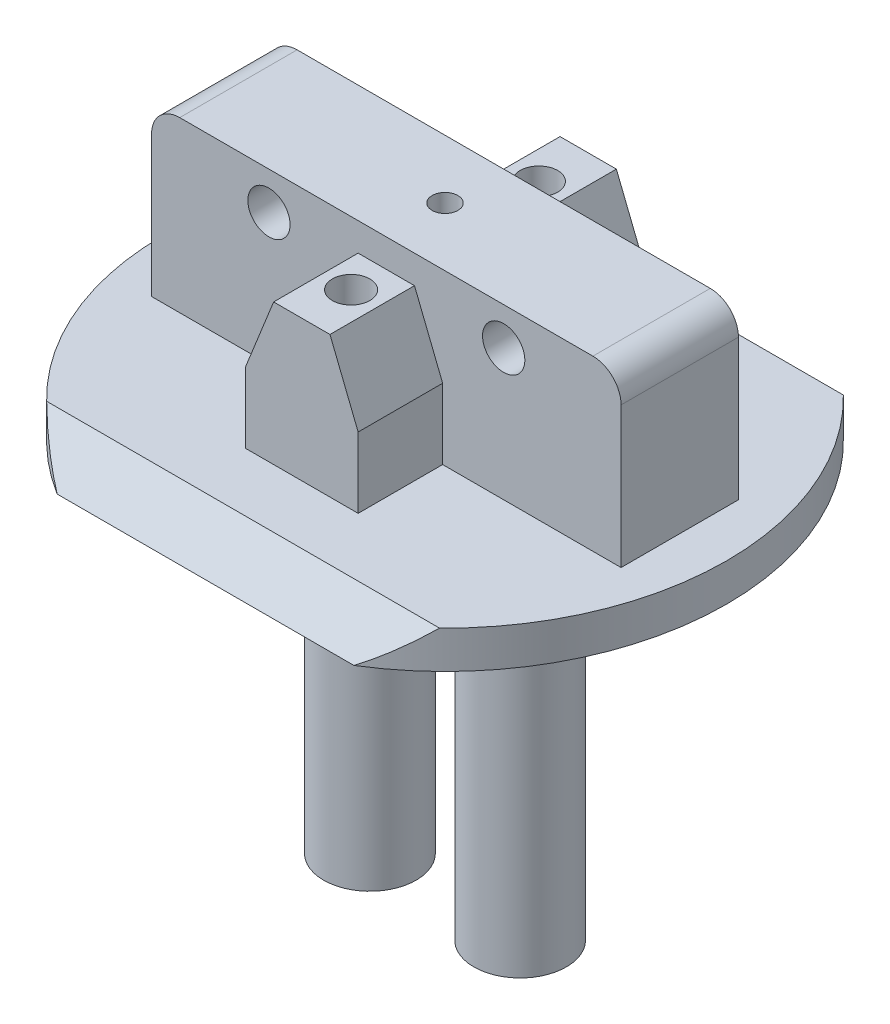
SolidWorks part; units mm, degrees
ref_plane "Front Plane" through (0, 0, 0) normal (0, 0, 1) x (1, 0, 0)
ref_plane "Top Plane" through (0, 0, 0) normal (0, 1, 0) x (1, 0, 0)
ref_plane "Right Plane" through (0, 0, 0) normal (1, 0, 0) x (0, 0, -1)
sketch "Sketch1" plane through (0, 0, 0) normal (0, 1, 0) x (1, 0, 0)
  circle A0 centre (0, 0) radius 30
extrude "Boss-Extrude1" add sketch "Sketch1" along normal blind 4
sketch "Sketch2" plane through (0, 0, 0) normal (1, 0, 0) x (0, 0, -1)
  line L0 (0, 4) -> (21.5, 4)
  line L1 (30, 4) -> (-30, 4) construction
  line L3 (0, 4) -> (-21.5, 4)
  line L5 (0, 4) -> (0, 19.5) construction
  line L6 (-9, 16.5) -> (-21.5, 4)
  line L7 (-9, 16.5) -> (9, 16.5)
  line L9 (9, 16.5) -> (21.5, 4)
  dimension "D1" = 12.5
  dimension "D2" = 45
  dimension "D3" = 21.5
  dimension "D4" = 21.5
  dimension "D5" = 45
sketch "Sketch3" plane through (0, 4, 0) normal (0, 1, 0) x (1, 0, 0)
  circle A0 centre (0, 0) radius 21.5
  dimension "D1" = 43
extrude "Boss-Extrude2" add sketch "Sketch2" along normal up to surface and the other way up to surface up to face at (0, 4, 30) other way up to face at (0, 4, 30)
ref_plane "Plane1" through (0, 12.75, -12.75) normal (0, 0.7071, -0.7071) x (1, 0, 0)
other "SurfaceCut1"
ref_plane "Plane2" through (0, 12.75, 12.75) normal (0, 0.7071, 0.7071) x (1, 0, 0)
other "SurfaceCut2"
extrude "Cut-Extrude2" cut sketch "Sketch3" against normal up to surface (12.5 mm away) flip side to cut contours A0
sketch "Sketch5" plane through (0, 0, 0) normal (0, -1, 0) x (-1, 0, 0)
  line L0 (0, 0) -> (0, -6)
  line L1 (0, -6) -> (-17.5, -6)
  line L2 (-17.5, -6) -> (-17.5, 6)
  line L3 (-17.5, 6) -> (17.5, 6)
  line L4 (17.5, 6) -> (17.5, -6)
  line L5 (17.5, -6) -> (0, -6)
  circle A0 centre (0, 0) radius 6
  circle A1 centre (0, 0) radius 3.5
  dimension "D1" = 12
  dimension "D2" = 7
  dimension "D3" = 12
  dimension "D4" = 6
  dimension "D5" = 35
  dimension "D6" = 17.5
extrude "Boss-Extrude3" add sketch "Sketch5" along normal blind 18 contours L1 L2 L3 L4 L5
sketch "Sketch6" plane through (0, 0, 0) normal (0, -1, 0) x (1, 0, 0)
  line L0 (0, 6) -> (0, 15) construction
  line L1 (-17.5, 6) -> (17.5, 6) construction
  line L2 (0, 15) -> (7, 15)
  line L3 (7, 15) -> (7, 6)
  line L4 (-17.5, 6) -> (17.5, 6) construction
  line L5 (7, 6) -> (-7, 6)
  line L6 (-7, 6) -> (-7, 15)
  line L7 (-7, 15) -> (0, 15)
  dimension "D1" = 14
  dimension "D2" = 9
extrude "Boss-Extrude4" add sketch "Sketch6" along normal blind 15 contours L7 L2 L3 L5 L6
sketch "Sketch7" plane through (0, 0, 0) normal (0, -1, 0) x (1, 0, 0)
  line L0 (0, -6) -> (0, -15) construction
  line L1 (17.5, -6) -> (-17.5, -6) construction
  line L2 (0, -15) -> (7, -15)
  line L3 (7, -15) -> (7, -6)
  line L4 (7, -6) -> (-7, -6)
  line L7 (-7, -6) -> (-7, -15)
  line L8 (-7, -15) -> (0, -15)
  dimension "D1" = 9
  dimension "D2" = 14
extrude "Boss-Extrude5" add sketch "Sketch7" along normal blind 15
sketch "Sketch8" plane through (0, 0, 0) normal (0, 0, 1) x (1, 0, 0)
  line L0 (0, 0) -> (12.5, 0) construction
  line L1 (12.5, 0) -> (12.5, -12.5) construction
  line L2 (12.5, -12.5) -> (-12.5, -12.5) construction
  line L3 (-12.5, -12.5) -> (-12.5, 0) construction
  line L4 (-12.5, 0) -> (0, 0) construction
  circle A0 centre (-12.5, -12.5) radius 2
  circle A1 centre (12.5, -12.5) radius 2
  dimension "D4" = 4
  dimension "D5" = 4
  dimension "D1" = 12.5
  dimension "D2" = 25
  dimension "D3" = 12.5
extrude "Cut-Extrude3" cut sketch "Sketch8" against normal through all both and the other way through all contours A0 | A1
ref_plane "Plane3" through (0, -18, 0) normal (0, -1, 0) x (-1, 0, 0)
ref_plane "Plane4" through (10.366, -9.6749, -8.0624) normal (0.6355, -0.5931, -0.4943) x (-0.3613, 0.3373, -0.8693)
ref_plane "Plane5" through (-10.366, -9.6749, -8.0624) normal (0.6355, 0.5931, 0.4943) x (0.3613, 0.3373, -0.8693)
ref_plane "Plane6" through (10.366, -9.6749, 8.0624) normal (-0.6355, 0.5931, -0.4943) x (-0.3613, 0.3373, 0.8693)
ref_plane "Plane7" through (-10.366, -9.6749, 8.0624) normal (0.6355, 0.5931, -0.4943) x (-0.3613, -0.3373, -0.8693)
ref_plane "Plane9" through (0, 0, 6) normal (0, 0, 1) x (1, 0, 0)
sketch "Sketch16" plane through (0, 0, 6) normal (0, 0, 1) x (1, 0, 0)
  line L0 (17.5, -18) -> (17.5, -14.5)
  line L1 (-6.6, -18) -> (6.6, -18) construction
  line L2 (17.5, -18) -> (17.5, 0) construction
  line L3 (17.5, -18) -> (14, -18)
  line L4 (17.5, -14.5) -> (14, -18)
  line L5 (-17.5, -18) -> (-14, -18)
  line L6 (-17.5, -18) -> (-17.5, 0) construction
  line L7 (-14, -18) -> (-17.5, -14.5)
  line L8 (-17.5, -14.5) -> (-17.5, -18)
  dimension "D2" = 3.5
extrude "Cut-Extrude8" cut sketch "Sketch16" against normal through all both and the other way through all
sketch "Sketch17" plane through (10.366, -9.6749, -8.0624) normal (0.6355, -0.5931, -0.4943) x (-0.3613, 0.3373, -0.8693)
  line L0 (-2.3725, -6.1896) -> (7.9806, -0.7067)
  line L1 (5.4512, -6.1896) -> (10.5101, 4.7762) construction
  line L2 (7.9806, -0.7067) -> (7.9806, -10.9658)
  line L3 (10.5101, -15.7421) -> (5.4512, -6.1896) construction
  line L4 (7.9806, -10.9658) -> (-2.3725, -6.1896)
extrude "Cut-Extrude9" cut sketch "Sketch17" along normal through all
sketch "Sketch19" plane through (-10.366, -9.6749, -8.0624) normal (0.6355, 0.5931, 0.4943) x (0.3613, 0.3373, -0.8693)
  line L0 (-2.3725, -6.1896) -> (7.9806, -10.9658)
  line L1 (7.9806, -10.9658) -> (7.9806, -0.7067)
  line L2 (5.4512, -6.1896) -> (10.5101, 4.7762) construction
  line L3 (7.9806, -0.7067) -> (-2.3725, -6.1896)
extrude "Cut-Extrude11" cut sketch "Sketch19" against normal blind 20 contours L3 L0 L1
sketch "Sketch20" plane through (-10.366, -9.6749, 8.0624) normal (0.6355, 0.5931, -0.4943) x (-0.3613, -0.3373, -0.8693)
  line L0 (2.3725, -6.1896) -> (-7.9806, -0.7067)
  line L1 (-5.4512, -6.1896) -> (-10.5101, 4.7762) construction
  line L2 (-7.9806, -0.7067) -> (-7.9806, -10.9658)
  line L3 (-5.4512, -6.1896) -> (-10.5101, -15.7421) construction
  line L4 (-7.9806, -10.9658) -> (2.3725, -6.1896)
extrude "Cut-Extrude12" cut sketch "Sketch20" against normal blind 20
sketch "Sketch21" plane through (10.366, -9.6749, 8.0624) normal (-0.6355, 0.5931, -0.4943) x (-0.3613, 0.3373, 0.8693)
  line L0 (-2.3725, -6.1896) -> (7.9806, -0.7067)
  line L1 (5.4512, -6.1896) -> (10.5101, 4.7762) construction
  line L2 (7.9806, -0.7067) -> (7.9806, -10.9658)
  line L3 (7.9806, -10.9658) -> (-2.3725, -6.1896)
extrude "Cut-Extrude13" cut sketch "Sketch21" against normal blind 20 contours L0 L2 L3
ref_plane "Plane10" through (0, 16.5, 0) normal (0, 1, 0) x (1, 0, 0)
sketch "Sketch25" plane through (0, 0, 0) normal (0, 0, 1) x (1, 0, 0)
  line L1 (-33.0377, 0) -> (33.0377, 0)
  line L2 (-33.0377, 0) -> (-33.0377, -20.1422)
  line L3 (-33.0377, -20.1422) -> (33.0377, -20.1422)
  line L4 (33.0377, 0) -> (33.0377, -20.1422)
  dimension "D1" = 20.1422
  dimension "D2" = 66.0754
extrude "Cut-Extrude14" cut sketch "Sketch25" along normal through all both and the other way through all
sketch "Sketch26" plane through (0, 16.5, 0) normal (0, 1, 0) x (1, 0, 0)
  line L0 (-12.1, 0) -> (12.1, 0) construction
  circle A0 centre (-8, 0) radius 5
  circle A2 centre (8, 0) radius 5
  dimension "D1" = 10
  dimension "D2" = 10
  dimension "D3" = 8
  dimension "D4" = 8
sketch "Sketch27" plane through (0, 16.5, 0) normal (0, 1, 0) x (1, 0, 0)
  line L0 (0, -9.075) -> (0, 9.075) construction
  circle A0 centre (0, 0) radius 1.375
  dimension "D1" = 2.75
  dimension "D2" = 0
extrude "Cut-Extrude16" cut sketch "Sketch27" against normal blind 30
sketch "Sketch28" plane through (0, 0, 0) normal (0, -1, 0) x (1, 0, 0)
  line L0 (0, -9.075) -> (0, 9.075) construction
  line L1 (9.075, 0) -> (-9.075, 0) construction
  circle A0 centre (0, -15) radius 5
  circle A1 centre (22, 0) radius 5
  circle A2 centre (0, 15) radius 5
  circle A3 centre (-22, 0) radius 5
  circle A4 centre (-14, 12) radius 5
  circle A5 centre (14, 12) radius 5
  circle A6 centre (14, -12) radius 5
  circle A7 centre (-14, -12) radius 5
  dimension "D1" = 10
  dimension "D2" = 10
  dimension "D3" = 10
  dimension "D4" = 10
  dimension "D5" = 10
  dimension "D6" = 10
  dimension "D7" = 10
  dimension "D10" = 10
  dimension "D11" = 15
  dimension "D8" = 22
  dimension "D9" = 22
  dimension "D12" = 15
  dimension "D13" = 14
  dimension "D14" = 14
  dimension "D15" = 14
  dimension "D16" = 14
  dimension "D17" = 12
  dimension "D18" = 12
  dimension "D19" = 12
  dimension "D20" = 12
extrude "Cut-Extrude17" cut sketch "Sketch28" against normal blind 3
sketch "Sketch29" plane through (0, 0, 0) normal (1, 0, 0) x (0, 0, -1)
  line L0 (-10.55, 14.95) -> (-14.95, 10.55) construction
  line L1 (-21.5, 4) -> (21.9126, 4)
  line L2 (-21.5, 4) -> (-21.5, 17.3262)
  line L3 (-21.5, 17.3262) -> (21.9126, 17.3262)
  line L4 (21.9126, 4) -> (21.9126, 17.3262)
  line L5 (21.5, 4) -> (-21.5, 4) construction
extrude "Cut-Extrude18" cut sketch "Sketch29" against normal through all both and the other way through all
sketch "Sketch32" plane through (0, 4, 0) normal (0, 1, 0) x (1, 0, 0)
  line L1 (-25, 6.25) -> (25, 6.25)
  line L2 (-25, 6.25) -> (-25, -6.25)
  line L3 (-25, -6.25) -> (25, -6.25)
  line L4 (25, 6.25) -> (25, -6.25)
  line L5 (-25, 6.25) -> (25, -6.25) construction
  line L6 (-25, -6.25) -> (25, 6.25) construction
  point P0 (0, 0)
  dimension "D1" = 12.5
  dimension "D2" = 50
extrude "Boss-Extrude6" add sketch "Sketch32" along normal blind 18
sketch "Sketch35" plane through (0, 0, -6.25) normal (0, 0, -1) x (-1, 0, 0)
  line L0 (-20.9225, 4) -> (20.9225, 4) construction
  line L1 (-6, 4) -> (6, 4)
  line L2 (-6, 4) -> (-6, 19)
  line L3 (-6, 19) -> (6, 19)
  line L4 (6, 4) -> (6, 19)
  line L5 (0, 9.075) -> (0, -9.075) construction
  dimension "D1" = 12
  dimension "D2" = 15
  dimension "D3" = 6
extrude "Boss-Extrude7" add sketch "Sketch35" along normal blind 9
sketch "Sketch36" plane through (0, 19, 0) normal (0, 1, 0) x (1, 0, 0)
  line L0 (0, -9.075) -> (0, 9.075) construction
  circle A0 centre (0, 10) radius 2
  dimension "D1" = 4
  dimension "D2" = 10
sketch "Sketch37" plane through (0, 0, -6.25) normal (0, 0, -1) x (-1, 0, 0)
  line L0 (0, 12.1) -> (0, -12.1) construction
  line L3 (-20.9225, 4) -> (20.9225, 4) construction
  line L4 (-6, 4) -> (6, 4) construction
  circle A0 centre (-12.5, 18) radius 2.25
  circle A1 centre (12.5, 18) radius 2.25
  dimension "D5" = 4.5
  dimension "D6" = 4.5
  dimension "D1" = 12.5
  dimension "D2" = 12.5
  dimension "D3" = 14
  dimension "D4" = 14
extrude "Cut-Extrude19" cut sketch "Sketch37" against normal through all both and the other way through all
extrude "Cut-Extrude20" cut sketch "Sketch36" against normal blind 15
sketch "Sketch39" plane through (0, 0, 6.25) normal (0, 0, 1) x (1, 0, 0)
  line L0 (-25, 4) -> (25, 4) construction
  line L1 (-6, 4) -> (6, 4)
  line L2 (-6, 4) -> (-6, 19)
  line L3 (-6, 19) -> (6, 19)
  line L4 (6, 4) -> (6, 19)
  line L5 (0, -12.1) -> (0, 12.1) construction
  dimension "D1" = 12
  dimension "D2" = 6
  dimension "D3" = 15
extrude "Boss-Extrude8" add sketch "Sketch39" along normal blind 9
sketch "Sketch40" plane through (0, 19, 0) normal (0, 1, 0) x (1, 0, 0)
  line L0 (0, -12.1) -> (0, 12.1) construction
  circle A0 centre (0, -10) radius 2
  dimension "D1" = 4
  dimension "D2" = 10
extrude "Cut-Extrude21" cut sketch "Sketch40" against normal blind 15
fillet "Fillet1" radius 3 1 edges at (25, 22, 0)
fillet "Fillet2" radius 3 1 edges at (-25, 22, 0)
sketch "Sketch44" plane through (0, 4, 0) normal (0, -1, 0) x (1, 0, 0)
  circle A0 centre (0, 0) radius 1.375
  dimension "D1" = 2.75
extrude "Cut-Extrude24" cut sketch "Sketch44" against normal blind 20
sketch "Sketch45" plane through (0, 0, 0) normal (0, -1, 0) x (1, 0, 0)
  circle A0 centre (-8, 0) radius 4.925
  circle A1 centre (8, 0) radius 4.925
  dimension "D1" = 9.85
  dimension "D2" = 9.85
extrude "Boss-Extrude9" add sketch "Sketch45" along normal blind 42
sketch "Sketch46" plane through (0, -42, 0) normal (0, -1, 0) x (1, 0, 0)
  circle A0 centre (-8, 0) radius 1.8923
  dimension "D1" = 3.7846
extrude "Cut-Extrude25" cut sketch "Sketch46" against normal blind 29.972
sketch "Sketch47" plane through (0, -42, 0) normal (0, -1, 0) x (1, 0, 0)
  circle A0 centre (8, 0) radius 1.8923
  dimension "D1" = 3.7846
extrude "Cut-Extrude26" cut sketch "Sketch47" against normal blind 29.972
sketch "Sketch58" plane through (0, 0, -15.25) normal (0, 0, -1) x (-1, 0, 0)
  line L0 (6, 19) -> (6, 11.5)
  line L1 (6, 4) -> (6, 19) construction
  line L2 (6, 11.5) -> (3, 19)
  line L3 (6, 19) -> (-6, 19) construction
  line L4 (3, 19) -> (6, 19)
  dimension "D1" = 3
extrude "Cut-Extrude32" cut sketch "Sketch58" against normal up to surface (9 mm away) up to face at (14.75, 18, -6.25)
sketch "Sketch59" plane through (0, 0, -15.25) normal (0, 0, -1) x (-1, 0, 0)
  line L0 (-6, 19) -> (-6, 11.5)
  line L1 (-6, 19) -> (-6, 4) construction
  line L2 (-6, 11.5) -> (-3, 19)
  line L3 (3, 19) -> (-6, 19) construction
  line L4 (-3, 19) -> (-6, 19)
  dimension "D1" = 3
extrude "Cut-Extrude33" cut sketch "Sketch59" against normal up to surface (9 mm away) up to face at (14.75, 18, -6.25)
sketch "Sketch60" plane through (0, 0, 15.25) normal (0, 0, 1) x (1, 0, 0)
  line L0 (6, 11.5) -> (6, 19)
  line L1 (6, 4) -> (6, 19) construction
  line L2 (6, 11.5) -> (3, 19)
  line L3 (6, 19) -> (-6, 19) construction
  line L4 (3, 19) -> (6, 19)
  dimension "D1" = 3
extrude "Cut-Extrude34" cut sketch "Sketch60" against normal up to surface (9 mm away) up to face at (-14.75, 18, 6.25)
sketch "Sketch61" plane through (0, 0, 15.25) normal (0, 0, 1) x (1, 0, 0)
  line L0 (-6, 19) -> (-6, 11.5)
  line L1 (-6, 19) -> (-6, 4) construction
  line L2 (-6, 11.5) -> (-3, 19)
  line L3 (3, 19) -> (-6, 19) construction
  line L4 (-3, 19) -> (-6, 19)
  dimension "D1" = 3
extrude "Cut-Extrude35" cut sketch "Sketch61" against normal up to surface (9 mm away) up to face at (-14.75, 18, 6.25)
